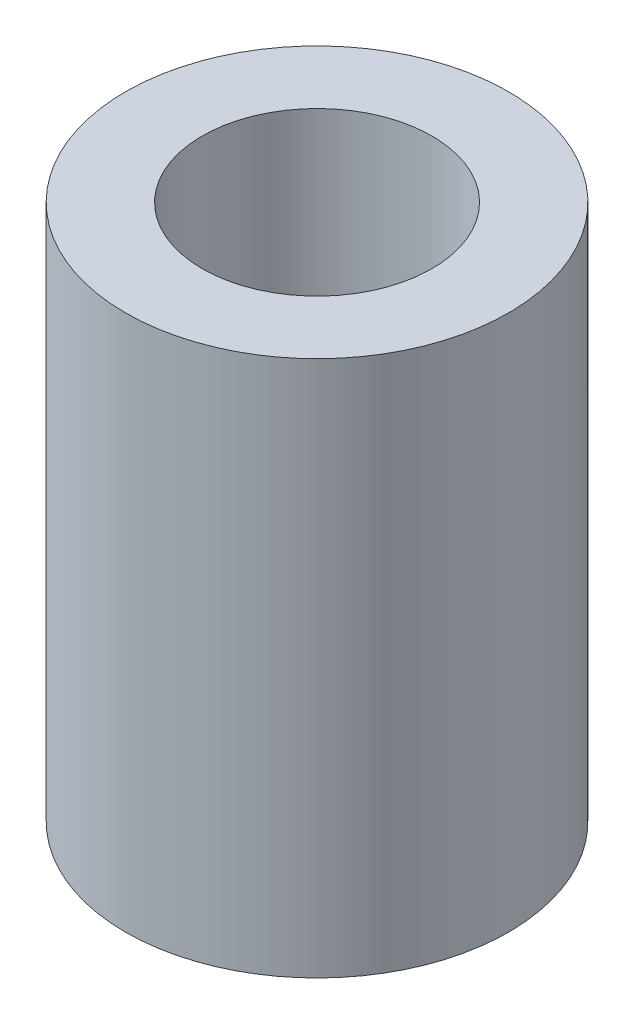
SolidWorks part; units mm, degrees
ref_plane "前视基准面" through (0, 0, 0) normal (0, 0, 1) x (1, 0, 0)
ref_plane "上视基准面" through (0, 0, 0) normal (0, 1, 0) x (1, 0, 0)
ref_plane "右视基准面" through (0, 0, 0) normal (1, 0, 0) x (0, 0, -1)
sketch "草图1" plane through (0, 0, 0) normal (0, 1, 0) x (1, 0, 0)
  circle A0 centre (0, 0) radius 1.5
  circle A1 centre (0, 0) radius 2.5
  dimension "D1" = 5
  dimension "D2" = 3
extrude "凸台-拉伸1" add sketch "草图1" along normal blind 7
